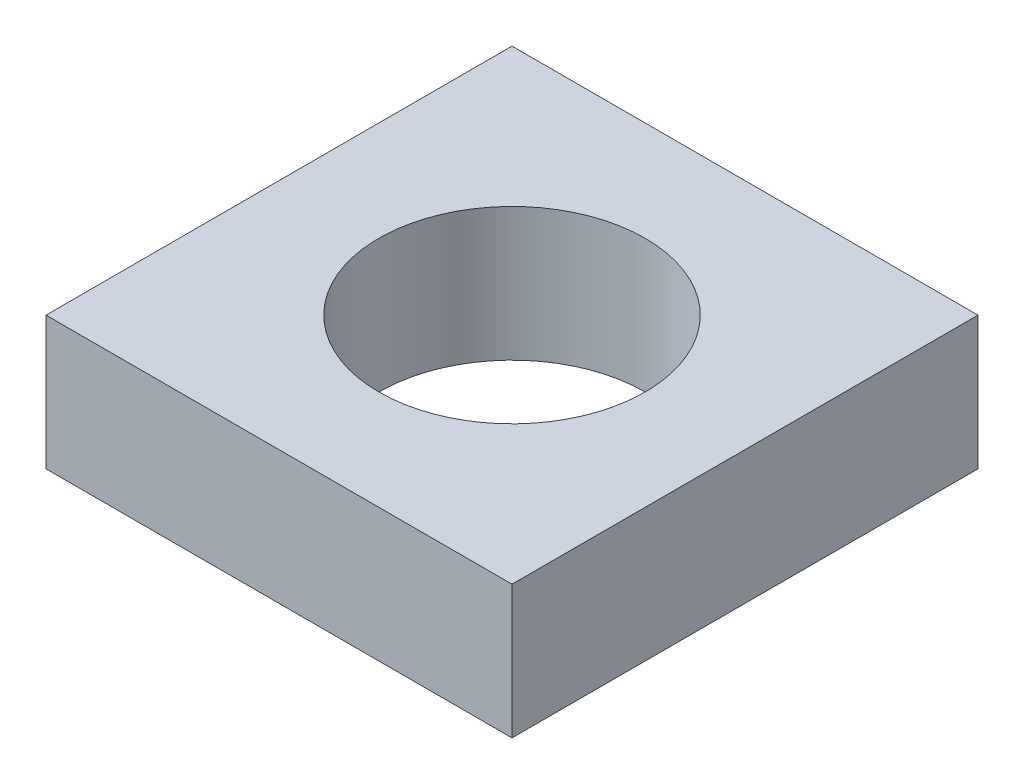
SolidWorks part; units mm, degrees
ref_plane "前视基准面" through (0, 0, 0) normal (0, 0, 1) x (1, 0, 0)
ref_plane "上视基准面" through (0, 0, 0) normal (0, 1, 0) x (1, 0, 0)
ref_plane "右视基准面" through (0, 0, 0) normal (1, 0, 0) x (0, 0, -1)
sketch "草图1" plane through (0, 0, 0) normal (0, 1, 0) x (1, 0, 0)
  line L1 (-3.5, 3.5) -> (3.5, 3.5)
  line L2 (-3.5, 3.5) -> (-3.5, -3.5)
  line L3 (-3.5, -3.5) -> (3.5, -3.5)
  line L4 (3.5, 3.5) -> (3.5, -3.5)
  line L5 (-3.5, 3.5) -> (3.5, -3.5) construction
  line L6 (-3.5, -3.5) -> (3.5, 3.5) construction
  circle A0 centre (0, 0) radius 2
  point P0 (0, 0)
  dimension "D2" = 4
  dimension "D1" = 7
extrude "凸台-拉伸1" add sketch "草图1" along normal blind 2
